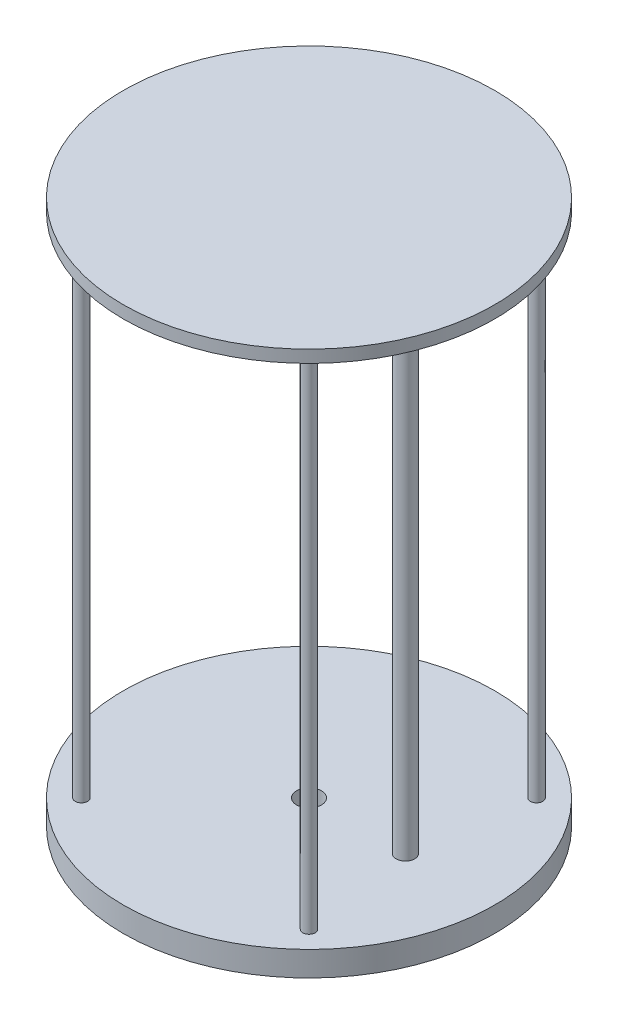
SolidWorks part; units mm, degrees
ref_plane "Front Plane" through (0, 0, 0) normal (0, 0, 1) x (1, 0, 0)
ref_plane "Top Plane" through (0, 0, 0) normal (0, 1, 0) x (1, 0, 0)
ref_plane "Right Plane" through (0, 0, 0) normal (1, 0, 0) x (0, 0, -1)
sketch "Sketch1" plane through (0, 0, 0) normal (0, 1, 0) x (1, 0, 0)
  circle A0 centre (0, 0) radius 75
  dimension "D1" = 150
extrude "Boss-Extrude1" add sketch "Sketch1" along normal blind 10
sketch "Sketch2" plane through (0, 10, 0) normal (0, 1, 0) x (1, 0, 0)
  line L0 (0, 75) -> (0, -75) construction
  line L1 (-45.9619, 45.9619) -> (0, 0) construction
  line L2 (0, 0) -> (45.9619, 45.9619) construction
  circle A0 centre (0, 0) radius 75 construction
  circle A1 centre (-45.9619, 45.9619) radius 2.5
  circle A2 centre (45.9619, 45.9619) radius 2.5
  circle A3 centre (45.9619, -45.9619) radius 2.5
  circle A4 centre (-45.9619, -45.9619) radius 2.5
  circle A5 centre (38.9619, 0) radius 3.75
  dimension "D1" = 5
  dimension "D6" = 7.5
  dimension "D2" = 45
  dimension "D3" = 65
  dimension "D5" = 90
  dimension "D7" = 7
  dimension "D4" = 4
extrude "Boss-Extrude2" add sketch "Sketch2" along normal blind 205
ref_plane "Plane1" through (0, 215, 0) normal (0, 1, 0) x (1, 0, 0)
sketch "Sketch3" plane through (0, 215, 0) normal (0, 1, 0) x (1, 0, 0)
  circle A0 centre (0, 0) radius 75
  dimension "D1" = 150
extrude "Boss-Extrude3" add sketch "Sketch3" along normal blind 5
sketch "Sketch4" plane through (0, 0, 0) normal (0, -1, 0) x (1, 0, 0)
  circle A0 centre (0, 0) radius 5
  dimension "D1" = 10
extrude "Cut-Extrude1" cut sketch "Sketch4" against normal up to next
equation "\"Platform Diameter\"= 150mm'Used in J1"
equation "\"Platform Thickness\"= 10mm"
equation "\"Guide Rod Diameter\"= 5mm'Used in J1"
equation "\"Elevator Height\" = 220mm"
equation "\"Top Thickness\"= 5mm"
equation "\"Guide Rod Length\"= \"Elevator Height\" - \"Platform Thickness\" - \"Top Thickness\""
equation "\"Elevator Screw Diameter\"= 7.5mm"
equation "\"D1@Sketch1\"=\"Platform Diameter\""
equation "\"D1@Boss-Extrude1\"=\"Platform Thickness\""
equation "\"D1@Sketch2\"=\"Guide Rod Diameter\""
equation "\"Guide Rod Offset\"= 10mm"
equation "\"D3@Sketch2\"=(\"Platform Diameter\"/2) - \"Guide Rod Offset\""
equation "\"D6@Sketch2\"=\"Elevator Screw Diameter\""
equation "\"D1@Boss-Extrude2\"=\"Guide Rod Length\""
equation "\"D1@Sketch3\"=\"Platform Diameter\""
equation "\"D1@Boss-Extrude3\"=\"Top Thickness\""
